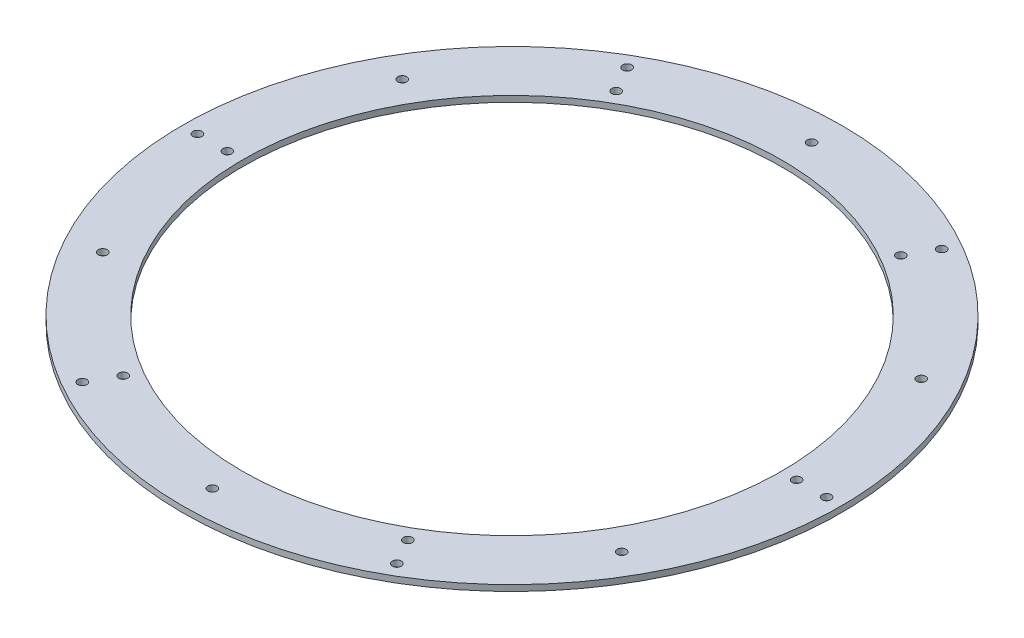
SolidWorks part; units mm, degrees
material "1060 Alloy"
ref_plane "Front Plane" through (0, 0, 0) normal (0, 0, 1) x (1, 0, 0)
ref_plane "Top Plane" through (0, 0, 0) normal (0, 1, 0) x (1, 0, 0)
ref_plane "Right Plane" through (0, 0, 0) normal (1, 0, 0) x (0, 0, -1)
sketch "Sketch1" plane through (0, 0, 0) normal (0, 1, 0) x (1, 0, 0)
  line L0 (0, 0) -> (92.2337, 0) construction
  line L1 (0, 0) -> (79.8767, 46.1168) construction
  circle A0 centre (0, 0) radius 90
  circle A1 centre (0, 0) radius 110
  circle A2 centre (95, 0) radius 1.5
  circle A3 centre (105, 0) radius 1.5
  circle A4 centre (86.6025, 50) radius 1.5
  circle A5 centre (86.6025, -50) radius 1.5
  circle A6 centre (52.5, -90.9327) radius 1.5
  circle A7 centre (47.5, -82.2724) radius 1.5
  circle A8 centre (0, -100) radius 1.5
  circle A9 centre (-52.5, -90.9327) radius 1.5
  circle A10 centre (-47.5, -82.2724) radius 1.5
  circle A11 centre (-86.6025, -50) radius 1.5
  circle A12 centre (-105, 0) radius 1.5
  circle A13 centre (-95, 0) radius 1.5
  circle A14 centre (-86.6025, 50) radius 1.5
  circle A15 centre (-52.5, 90.9327) radius 1.5
  circle A16 centre (-47.5, 82.2724) radius 1.5
  circle A17 centre (0, 100) radius 1.5
  circle A18 centre (52.5, 90.9327) radius 1.5
  circle A19 centre (47.5, 82.2724) radius 1.5
  point P9 (0, 0)
  point P45 (0, 0)
  dimension "D1" = 180
  dimension "D2" = 220
  dimension "D4" = 95
  dimension "D7" = 3
  dimension "D5" = 105
  dimension "D6" = 100
  dimension "D3" = 2
  dimension "D8" = 6
extrude "Boss-Extrude1" add sketch "Sketch1" along normal blind 2
